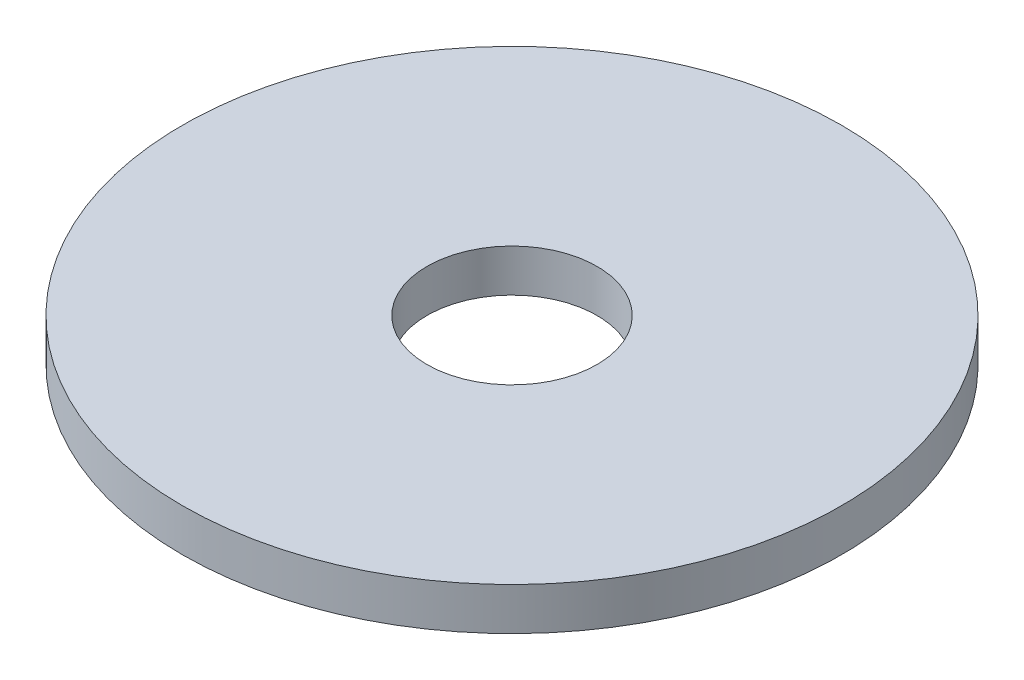
SolidWorks part; units mm, degrees
ref_plane "Front Plane" through (0, 0, 0) normal (0, 0, 1) x (1, 0, 0)
ref_plane "Top Plane" through (0, 0, 0) normal (0, 1, 0) x (1, 0, 0)
ref_plane "Right Plane" through (0, 0, 0) normal (1, 0, 0) x (0, 0, -1)
sketch "Sketch1" plane through (0, 0, 0) normal (0, 1, 0) x (1, 0, 0)
  circle A0 centre (0, 0) radius 15.5
  circle A1 centre (0, 0) radius 4
  dimension "D1" = 31
  dimension "D2" = 8
extrude "Boss-Extrude1" add sketch "Sketch1" along normal blind 2
